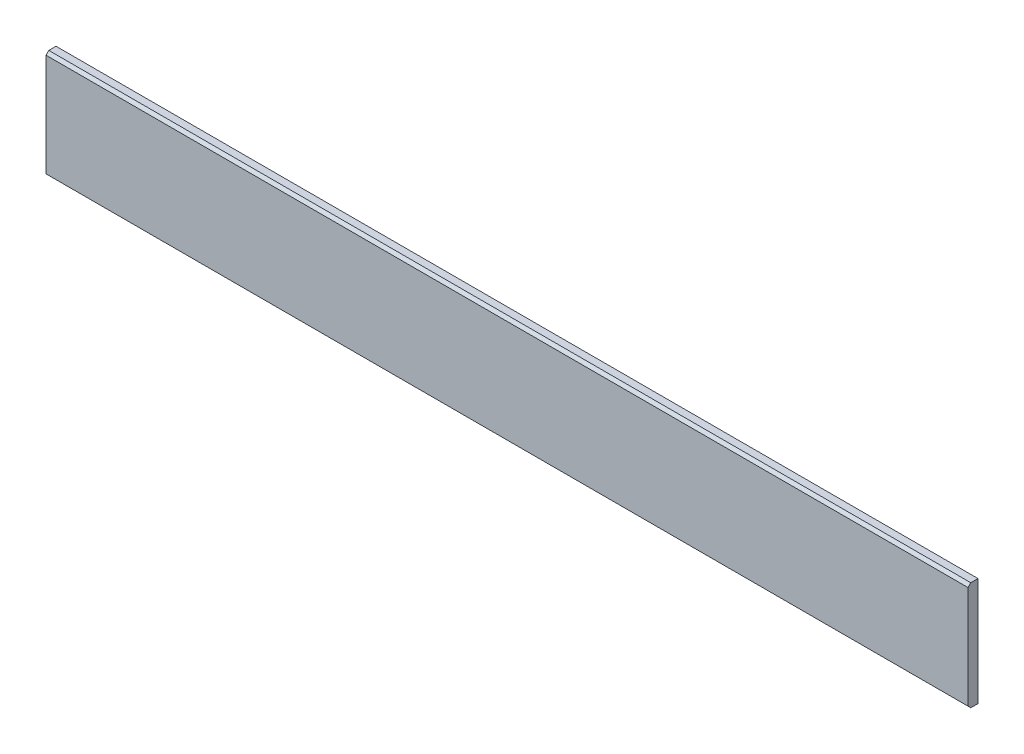
SolidWorks part; units mm, degrees
ref_plane "前视基准面" through (0, 0, 0) normal (0, 0, 1) x (1, 0, 0)
ref_plane "上视基准面" through (0, 0, 0) normal (0, 1, 0) x (1, 0, 0)
ref_plane "右视基准面" through (0, 0, 0) normal (1, 0, 0) x (0, 0, -1)
sketch "草图1" plane through (0, 0, 0) normal (0, 0, 1) x (1, 0, 0)
  line L1 (-830, 97.5) -> (830, 97.5)
  line L2 (-830, 97.5) -> (-830, -97.5)
  line L3 (-830, -97.5) -> (830, -97.5)
  line L4 (830, 97.5) -> (830, -97.5)
  line L5 (-830, 97.5) -> (830, -97.5) construction
  line L6 (-830, -97.5) -> (830, 97.5) construction
  point P0 (0, 0)
  dimension "D1" = 1660
  dimension "D2" = 195
extrude "凸台-拉伸1" add sketch "草图1" along normal blind 18
chamfer "倒角1" distance 5 angle 45 2 edges at (0, -97.5, 18) (0, 97.5, 18)
